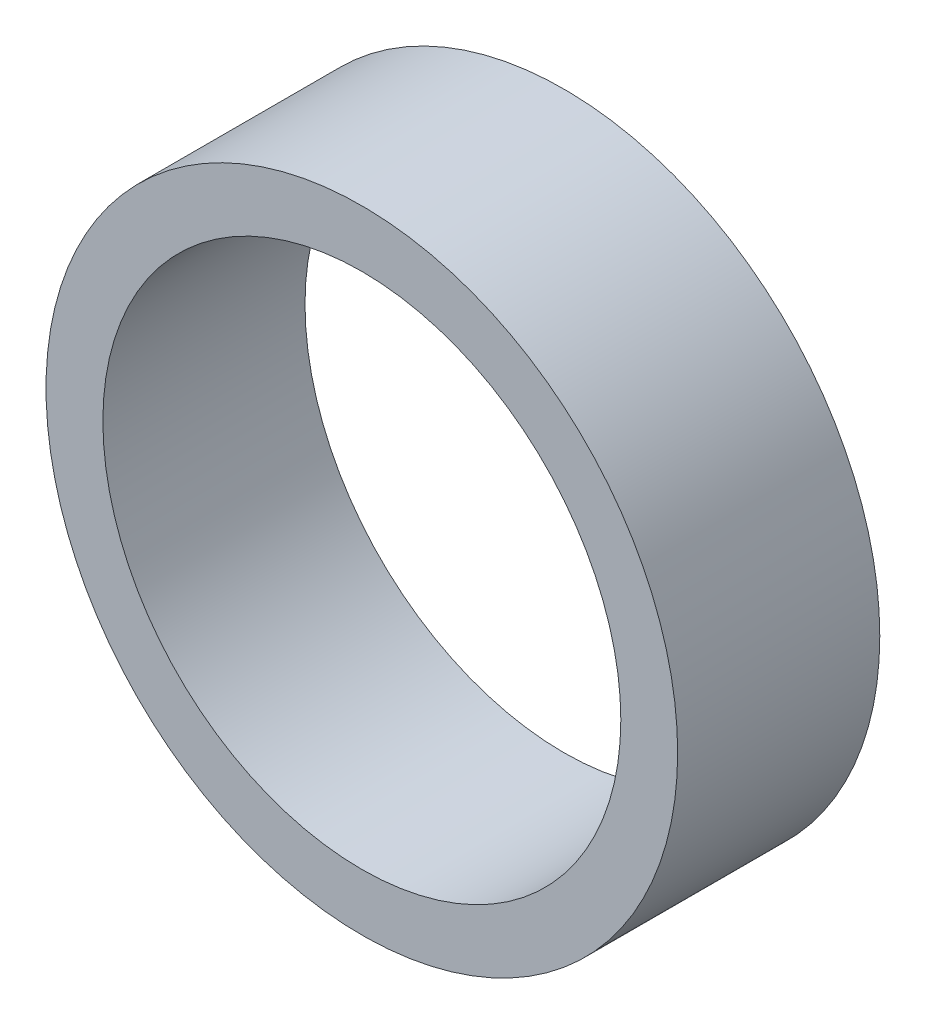
SolidWorks part; units mm, degrees
ref_plane "前视基准面" through (0, 0, 0) normal (0, 0, 1) x (1, 0, 0)
ref_plane "上视基准面" through (0, 0, 0) normal (0, 1, 0) x (1, 0, 0)
ref_plane "右视基准面" through (0, 0, 0) normal (1, 0, 0) x (0, 0, -1)
sketch "草图1" plane through (0, 0, 0) normal (0, 0, 1) x (1, 0, 0)
  circle A0 centre (0, 0) radius 10.25
  circle A1 centre (0, 0) radius 12.5
extrude "凸台-拉伸1" add sketch "草图1" along normal blind 8
